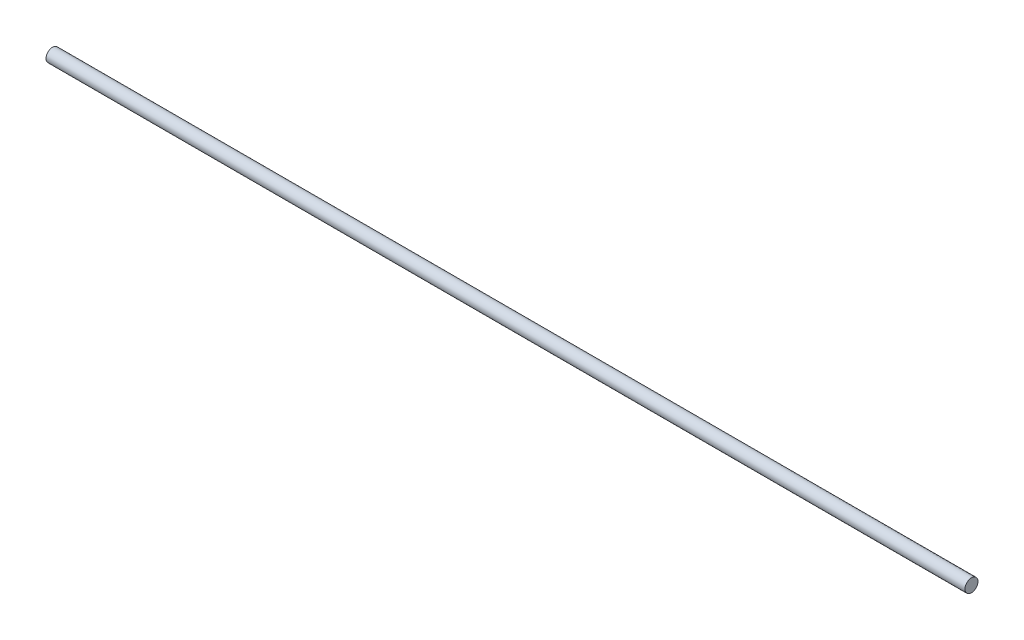
SolidWorks part; units mm, degrees
ref_plane "前视基准面" through (0, 0, 0) normal (0, 0, 1) x (1, 0, 0)
ref_plane "上视基准面" through (0, 0, 0) normal (0, 1, 0) x (1, 0, 0)
ref_plane "右视基准面" through (0, 0, 0) normal (1, 0, 0) x (0, 0, -1)
ref_plane "基准面4" through (0, 0, -33.5) normal (0, 0, 1) x (1, 0, 0)
sketch "草图1" plane through (0, 0, -33.5) normal (0, 0, 1) x (1, 0, 0)
  line L0 (-176, 334.0789) -> (-176, 331.5789)
  line L1 (-176, 331.5789) -> (176, 331.5789)
  line L2 (176, 331.5789) -> (176, 334.0789)
  line L3 (176, 334.0789) -> (-176, 334.0789)
  line L4 (-176, 331.5789) -> (176, 331.5789) construction
  line L5 (0, 0) -> (0, 439.954) construction
  dimension "D1" = 352
  dimension "D2" = 2.5
revolve "旋转1" add sketch "草图1" angle 360 about L4
